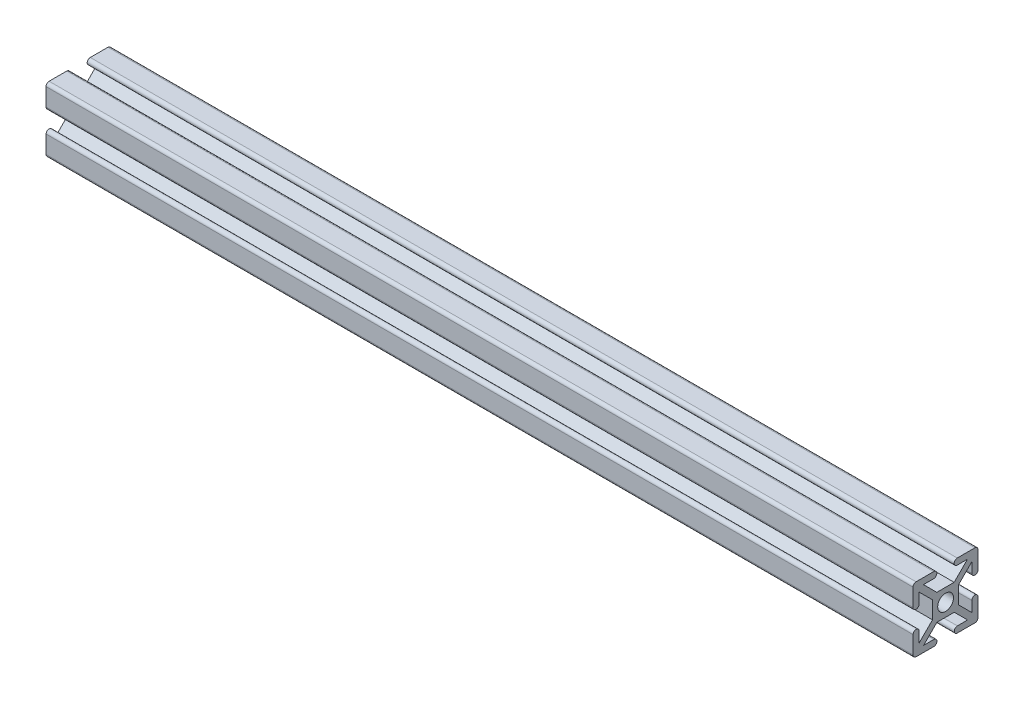
SolidWorks part; units mm, degrees
ref_plane "Alzado" through (0, 0, 0) normal (0, 0, 1) x (1, 0, 0)
ref_plane "Planta" through (0, 0, 0) normal (0, 1, 0) x (1, 0, 0)
ref_plane "Vista lateral" through (0, 0, 0) normal (1, 0, 0) x (0, 0, -1)
sketch "Croquis1" plane through (0, 0, 0) normal (1, 0, 0) x (0, 0, -1)
  line L0 (-17.459, 19.8349) -> (-17.459, 21.2599) construction
  line L1 (1.5939, 3.6849) -> (6.3189, 3.6849)
  line L2 (-18.884, 29.4098) -> (-18.884, 21.2599)
  line L3 (-17.459, 30.8348) -> (-9.309, 30.8348)
  line L4 (1.541, 30.8348) -> (9.691, 30.8348)
  line L5 (-13.9811, 3.6849) -> (-9.2561, 3.6849)
  line L6 (-9.884, 19.8349) -> (-9.884, 11.8349)
  line L7 (-18.8311, 10.4099) -> (-18.8311, 2.2599)
  line L8 (-17.4326, 0.8613) -> (-9.2561, 0.8349)
  line L9 (11.116, 29.4098) -> (11.116, 21.3636)
  line L10 (-16.034, 25.9849) -> (-16.034, 21.2599)
  line L11 (11.116, 10.5136) -> (11.116, 2.2599)
  line L12 (-7.884, 29.4098) -> (-9.309, 29.4098) construction
  line L13 (1.5939, 0.8349) -> (9.691, 0.8349)
  line L14 (-14.034, 27.9848) -> (-9.309, 27.9848)
  line L15 (-16.034, 10.4099) -> (-16.034, 5.6849)
  line L16 (0.116, 29.4098) -> (1.541, 29.4098) construction
  line L17 (1.541, 27.9848) -> (6.266, 27.9848)
  line L18 (9.691, 19.9386) -> (9.691, 21.3636) construction
  line L19 (-7.884, 21.8348) -> (-14.034, 27.9848)
  line L20 (8.266, 25.9848) -> (8.266, 21.3636)
  line L21 (9.691, 11.9386) -> (9.691, 10.5136) construction
  line L22 (-9.884, 19.8349) -> (-16.034, 25.9849)
  line L23 (8.266, 10.5136) -> (8.266, 5.6848)
  line L24 (0.1689, 2.2599) -> (1.5939, 2.2599) construction
  line L25 (-9.884, 11.8349) -> (-16.034, 5.6849)
  line L26 (-7.884, 21.8348) -> (0.116, 21.8348)
  line L27 (0.116, 21.8348) -> (6.266, 27.9848)
  line L28 (-17.4326, 11.8349) -> (-17.4326, 10.4099) construction
  line L29 (-13.9811, 3.6849) -> (-7.8311, 9.8349)
  line L30 (-7.8311, 9.8349) -> (0.1689, 9.8349)
  line L31 (0.1689, 9.8349) -> (6.3189, 3.6849)
  line L32 (-7.8311, 2.2599) -> (-9.2561, 2.2599) construction
  line L33 (2.116, 11.8348) -> (8.266, 5.6848)
  line L34 (2.116, 19.8348) -> (8.266, 25.9848)
  line L35 (2.116, 19.8348) -> (2.116, 11.8348)
  circle A0 centre (-3.8311, 15.8349) radius 3.645
  arc A1 (-18.884, 21.2599) -> (-16.034, 21.2599) centre (-17.459, 21.2599) ccw
  arc A2 (-9.309, 27.9848) -> (-9.309, 30.8348) centre (-9.309, 29.4098) ccw
  arc A3 (1.541, 30.8348) -> (1.541, 27.9848) centre (1.541, 29.4098) ccw
  arc A4 (8.266, 21.3636) -> (11.116, 21.3636) centre (9.691, 21.3636) ccw
  arc A5 (11.116, 10.5136) -> (8.266, 10.5136) centre (9.691, 10.5136) ccw
  arc A6 (1.5939, 3.6849) -> (1.5939, 0.8349) centre (1.5939, 2.2599) ccw
  arc A7 (-16.034, 10.4099) -> (-18.8311, 10.4099) centre (-17.4326, 10.4099) ccw
  arc A8 (-9.2561, 0.8349) -> (-9.2561, 3.6849) centre (-9.2561, 2.2599) ccw
  arc A9 (-18.8311, 2.2599) -> (-17.4326, 0.8613) centre (-17.4326, 2.2599) ccw
  arc A10 (9.691, 0.8349) -> (11.116, 2.2599) centre (9.691, 2.2599) ccw
  arc A11 (11.116, 29.4098) -> (9.691, 30.8348) centre (9.691, 29.4098) ccw
  arc A12 (-17.459, 30.8348) -> (-18.884, 29.4098) centre (-17.459, 29.4098) ccw
  dimension "D1" = 1.425
  dimension "D2" = 1.425
  dimension "D3" = 1.425
  dimension "D4" = 1.425
  dimension "D5" = 1.425
  dimension "D6" = 1.425
  dimension "D7" = 1.425
  dimension "D8" = 1.425
extrude "Saliente-Extruir1" add sketch "Croquis1" along normal blind 400
